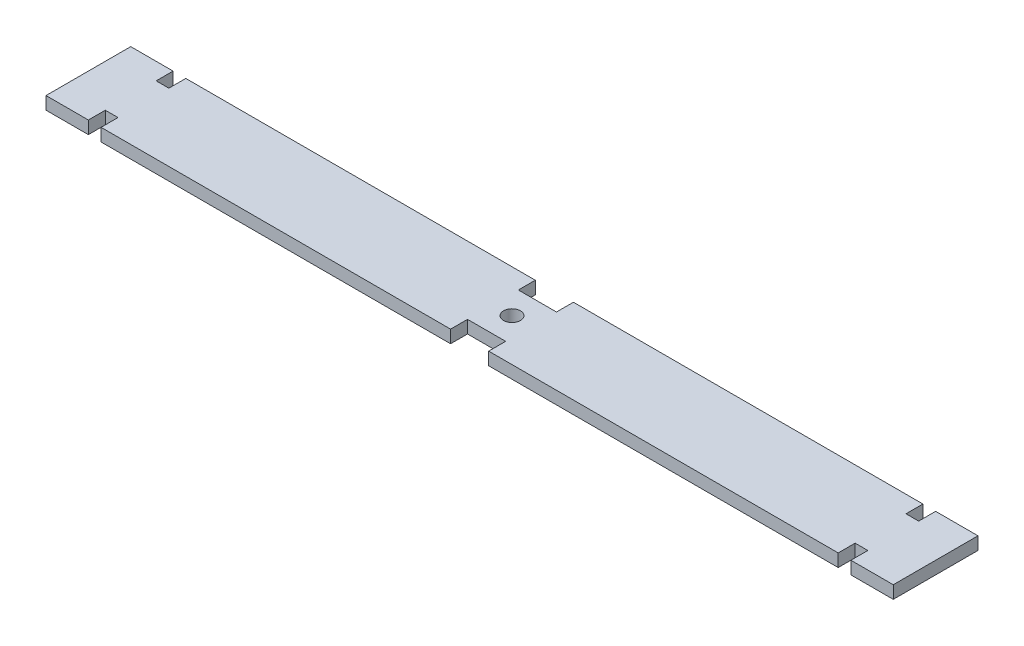
SolidWorks part; units mm, degrees
ref_plane "Front Plane" through (0, 0, 0) normal (0, 0, 1) x (1, 0, 0)
ref_plane "Top Plane" through (0, 0, 0) normal (0, 1, 0) x (1, 0, 0)
ref_plane "Right Plane" through (0, 0, 0) normal (1, 0, 0) x (0, 0, -1)
sketch "Sketch1" plane through (0, 0, 0) normal (0, 1, 0) x (1, 0, 0)
  line L1 (-9.8298, 5.8807) -> (90.1702, 5.8807)
  line L2 (-9.8298, 5.8807) -> (-9.8298, -4.1193)
  line L3 (-9.8298, -4.1193) -> (90.1702, -4.1193)
  line L4 (90.1702, 5.8807) -> (90.1702, -4.1193)
  dimension "D1" = 10
  dimension "D2" = 100
extrude "Boss-Extrude1" add sketch "Sketch1" along normal blind 1.5
sketch "Sketch2" plane through (0, 1.5, 0) normal (0, 1, 0) x (1, 0, 0)
  line L4 (90.1702, 5.8807) -> (-9.8298, 5.8807) construction
  line L5 (40.1702, 5.8807) -> (40.1702, -4.1193) construction
  line L6 (-9.8298, 0.8807) -> (90.1702, 0.8807) construction
  line L7 (-9.8298, 5.8807) -> (-9.8298, -4.1193) construction
  line L8 (90.1702, -4.1193) -> (90.1702, 5.8807) construction
  circle A0 centre (40.1702, 0.8807) radius 1
  dimension "D1" = 2
extrude "Cut-Extrude2" cut sketch "Sketch2" against normal blind 2 contours A0
sketch "Sketch5" plane through (0, 1.5, 0) normal (0, 1, 0) x (1, 0, 0)
  line L0 (90.1702, 5.8807) -> (-9.8298, 5.8807) construction
  line L1 (-4.8298, 5.8807) -> (-3.3298, 5.8807)
  line L2 (-4.8298, 5.8807) -> (-4.8298, 3.8807)
  line L3 (-4.8298, 3.8807) -> (-3.3298, 3.8807)
  line L4 (-3.3298, 5.8807) -> (-3.3298, 3.8807)
  line L5 (-9.8298, -4.1193) -> (90.1702, -4.1193) construction
  line L6 (37.9202, 5.8807) -> (42.4202, 5.8807)
  line L7 (37.9202, 5.8807) -> (37.9202, 3.8807)
  line L8 (37.9202, 3.8807) -> (42.4202, 3.8807)
  line L9 (42.4202, 5.8807) -> (42.4202, 3.8807)
  line L10 (83.6702, 5.8807) -> (85.1702, 5.8807)
  line L11 (83.6702, 5.8807) -> (83.6702, 3.8807)
  line L12 (83.6702, 3.8807) -> (85.1702, 3.8807)
  line L13 (85.1702, 5.8807) -> (85.1702, 3.8807)
  line L14 (-4.8298, -4.1193) -> (-3.3298, -4.1193)
  line L15 (-4.8298, -4.1193) -> (-4.8298, -2.1193)
  line L16 (-4.8298, -2.1193) -> (-3.3298, -2.1193)
  line L17 (-3.3298, -4.1193) -> (-3.3298, -2.1193)
  line L18 (-9.8298, 5.8807) -> (-9.8298, -4.1193) construction
  line L19 (37.9202, -4.1193) -> (42.4202, -4.1193)
  line L20 (37.9202, -4.1193) -> (37.9202, -2.1193)
  line L21 (37.9202, -2.1193) -> (42.4202, -2.1193)
  line L22 (42.4202, -4.1193) -> (42.4202, -2.1193)
  line L23 (83.6702, -4.1193) -> (85.1702, -4.1193)
  line L24 (83.6702, -4.1193) -> (83.6702, -2.1193)
  line L25 (83.6702, -2.1193) -> (85.1702, -2.1193)
  line L26 (85.1702, -4.1193) -> (85.1702, -2.1193)
  line L27 (90.1702, -4.1193) -> (90.1702, 5.8807) construction
  line L28 (40.1702, -4.1193) -> (40.1702, 5.8807) construction
  dimension "D1" = 1.5
  dimension "D2" = 5
  dimension "D3" = 2
  dimension "D4" = 5
  dimension "D5" = 2.25
  dimension "D6" = 4.5
  dimension "D7" = 1.5
extrude "Cut-Extrude4" cut sketch "Sketch5" against normal blind 2
